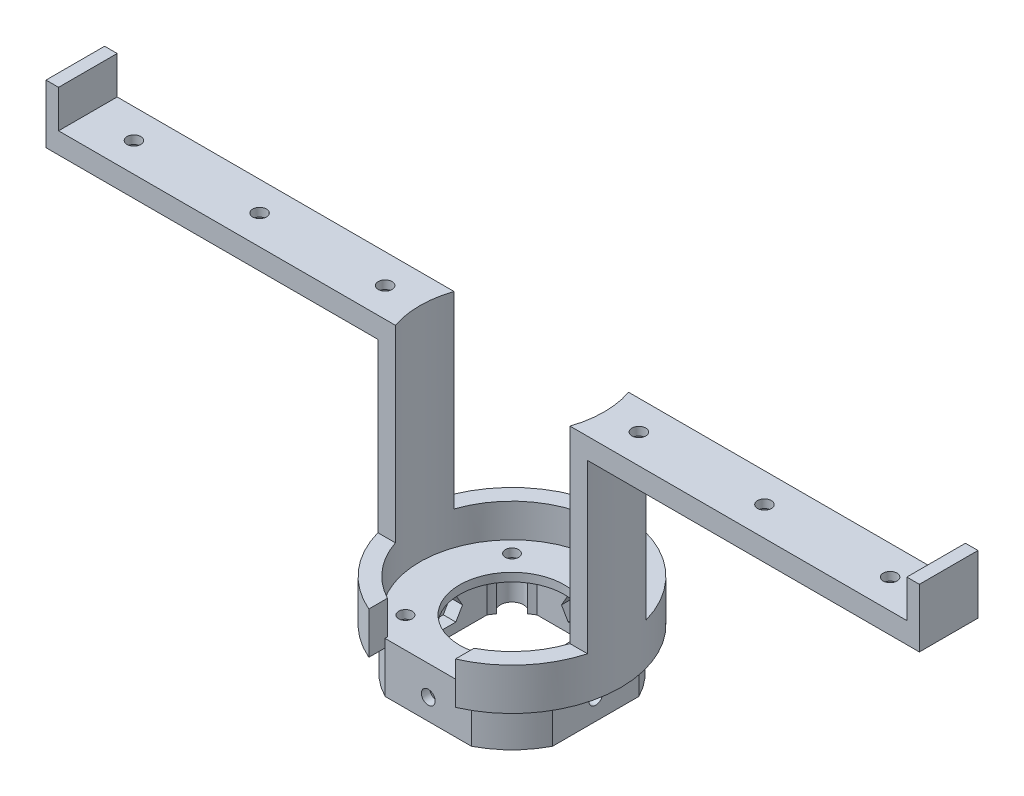
SolidWorks part; units mm, degrees
ref_plane "前视基准面" through (0, 0, 0) normal (0, 0, 1) x (1, 0, 0)
ref_plane "上视基准面" through (0, 0, 0) normal (0, 1, 0) x (1, 0, 0)
ref_plane "右视基准面" through (0, 0, 0) normal (1, 0, 0) x (0, 0, -1)
sketch "草图1" plane through (0, 0, 0) normal (0, 1, 0) x (1, 0, 0)
  line L0 (0, 0) -> (0, 18) construction
  line L1 (0, 0) -> (12.7279, 12.7279) construction
  line L2 (-32.6893, 0) -> (36.6315, 0) construction
  arc A0 (-20.3411, 8.381) -> (20.3411, 8.381) centre (0, 0) ccw
  circle A1 centre (0, 0) radius 18 construction
  circle A2 centre (12.7279, 12.7279) radius 1.6
  circle A3 centre (12.7279, -12.7279) radius 1.6
  circle A4 centre (-12.7279, -12.7279) radius 1.6
  circle A5 centre (-12.7279, 12.7279) radius 1.6
  circle A6 centre (0, 0) radius 22
  arc A7 (20.3411, 8.381) -> (-20.3411, 8.381) centre (0, 0) ccw
  point P16 (0, 0)
  dimension "D1" = 44
  dimension "D2" = 36
  dimension "D3" = 45
  dimension "D4" = 3.2
  dimension "D5" = 4
extrude "凸台-拉伸1" add sketch "草图1" along normal blind 2 contours A0 A6 A2 A3 A4 A5
sketch "草图2" plane through (0, 2, 0) normal (0, 1, 0) x (1, 0, 0)
  circle A1 centre (0, 0) radius 12.5
  dimension "D1" = 25
extrude "切除-拉伸1" cut sketch "草图2" against normal blind 3 contours A1
sketch "草图5" plane through (0, 0, 0) normal (0, 1, 0) x (1, 0, 0)
  line L6 (0, 27.5) -> (0, -27.5) construction
  circle A1 centre (0, 0) radius 22
  circle A3 centre (0, 0) radius 26
  dimension "D3" = 44
  dimension "D1" = 52
extrude "凸台-拉伸3" add sketch "草图5" along normal blind 10
sketch "草图14" plane through (0, 0, 0) normal (0, -1, 0) x (1, 0, 0)
  line L0 (-10.3078, 20) -> (10.3078, 20)
  line L1 (20, 10.3078) -> (20, -10.3078)
  line L2 (-10.3078, -20) -> (10.3078, -20)
  line L3 (-20, -10.3078) -> (-20, 10.3078)
  line L4 (-9.0139, 15) -> (9.0139, 15)
  line L5 (15, 9.0139) -> (15, -9.0139)
  line L6 (-15, 9.0139) -> (-15, -9.0139)
  line L7 (-9.0139, -15) -> (9.0139, -15)
  arc A0 (-10.3078, 20) -> (-20, 10.3078) centre (0, 0) ccw
  arc A1 (20, 10.3078) -> (10.3078, 20) centre (0, 0) ccw
  arc A2 (10.3078, -20) -> (20, -10.3078) centre (0, 0) ccw
  arc A3 (-20, -10.3078) -> (-10.3078, -20) centre (0, 0) ccw
  arc A4 (-15, -9.0139) -> (-14.1106, -10.3508) centre (0, 0) ccw
  arc A5 (-9.0139, 15) -> (-10.3508, 14.1106) centre (0, 0) ccw
  arc A6 (15, 9.0139) -> (14.1106, 10.3508) centre (0, 0) ccw
  arc A7 (9.0139, -15) -> (10.3508, -14.1106) centre (0, 0) ccw
  arc A8 (-10.3508, 14.1106) -> (-14.1106, 10.3508) centre (-12.7279, 12.7279) ccw
  arc A9 (14.1106, 10.3508) -> (10.3508, 14.1106) centre (12.7279, 12.7279) ccw
  arc A10 (-14.1106, -10.3508) -> (-10.3508, -14.1106) centre (-12.7279, -12.7279) ccw
  arc A11 (10.3508, -14.1106) -> (14.1106, -10.3508) centre (12.7279, -12.7279) ccw
  arc A12 (-14.1106, 10.3508) -> (-15, 9.0139) centre (0, 0) ccw
  arc A13 (10.3508, 14.1106) -> (9.0139, 15) centre (0, 0) ccw
  arc A14 (-10.3508, -14.1106) -> (-9.0139, -15) centre (0, 0) ccw
  arc A15 (14.1106, -10.3508) -> (15, -9.0139) centre (0, 0) ccw
  dimension "D1" = 45
  dimension "D6" = 35
  dimension "D11" = 5.5
  dimension "D12" = 5.5
  dimension "D13" = 5.5
  dimension "D14" = 5.5
  dimension "D2" = 20
  dimension "D3" = 20
  dimension "D4" = 20
  dimension "D5" = 20
  dimension "D7" = 5
  dimension "D8" = 5
  dimension "D9" = 5
  dimension "D10" = 5
extrude "凸台-拉伸5" add sketch "草图14" along normal blind 10
sketch "草图15" plane through (-20, 0, 0) normal (-1, 0, 0) x (0, 0, 1)
  line L0 (10.3078, 0) -> (-10.3078, 0) construction
  line L3 (0, 0) -> (0, -10) construction
  line L4 (10.3078, -10) -> (-10.3078, -10) construction
  circle A0 centre (0, -5) radius 1.65
  dimension "D1" = 3.3
  dimension "D2" = 5
extrude "切除-拉伸2" cut sketch "草图15" against normal blind 42
sketch "草图16" plane through (0, 0, -20) normal (0, 0, -1) x (-1, 0, 0)
  line L0 (10.3078, 0) -> (-10.3078, 0) construction
  line L1 (0, 0) -> (0, -10) construction
  line L2 (10.3078, -10) -> (-10.3078, -10) construction
  circle A0 centre (0, -5) radius 1.65
  dimension "D1" = 3.3
  dimension "D2" = 5
extrude "切除-拉伸3" cut sketch "草图16" against normal blind 42
sketch "草图18" plane through (0, 0, 0) normal (0, 0, 1) x (1, 0, 0)
  line L1 (-1.5877, -2.25) -> (-3.1754, -5)
  line L2 (-3.1754, -5) -> (-1.5877, -7.75)
  line L3 (-1.5877, -7.75) -> (1.5877, -7.75)
  line L4 (1.5877, -7.75) -> (3.1754, -5)
  line L5 (3.1754, -5) -> (1.5877, -2.25)
  line L6 (1.5877, -2.25) -> (-1.5877, -2.25)
  circle A0 centre (0, -5) radius 2.75 construction
  dimension "D1" = 5.5
extrude "切除-拉伸4" cut sketch "草图18" against normal mid plane 36
sketch "草图19" plane through (0, 0, 0) normal (1, 0, 0) x (0, 0, -1)
  line L1 (-1.5877, -2.25) -> (-3.1754, -5)
  line L2 (-3.1754, -5) -> (-1.5877, -7.75)
  line L3 (-1.5877, -7.75) -> (1.5877, -7.75)
  line L4 (1.5877, -7.75) -> (3.1754, -5)
  line L5 (3.1754, -5) -> (1.5877, -2.25)
  line L6 (1.5877, -2.25) -> (-1.5877, -2.25)
  circle A0 centre (0, -5) radius 2.75 construction
  dimension "D1" = 5.5
extrude "切除-拉伸5" cut sketch "草图19" against normal mid plane 36
sketch "草图23" plane through (0, 10, 0) normal (0, 1, 0) x (1, 0, 0)
  line L0 (-20.8567, 7) -> (-25.04, 7)
  line L1 (-26, 0) -> (26, 0) construction
  line L2 (-20.8567, -7) -> (-25.04, -7)
  line L3 (20.8567, 7) -> (25.04, 7)
  line L4 (20.8567, -7) -> (25.04, -7)
  circle A0 centre (0, 0) radius 22 construction
  circle A1 centre (0, 0) radius 26 construction
  circle A2 centre (0, 0) radius 26
  circle A3 centre (0, 0) radius 22 construction
  circle A4 centre (0, 0) radius 22
  circle M8 centre (0, 0) radius 26
  circle M9 centre (0, 0) radius 22
  dimension "D1" = 7
  dimension "D2" = 7
  dimension "D3" = 7
extrude "凸台-拉伸6" add sketch "草图23" along normal blind 45 contours L1 A4 L0 M8 | L1 A2 L2 M9 | L1 A2 L3 M9 | L1 A4 L4 M8
sketch "草图24" plane through (0, 55, 0) normal (0, 1, 0) x (1, 0, 0)
  line L0 (-20.8567, 7) -> (-25.04, 7) construction
  line L1 (-25.04, -7) -> (-75.3, -7)
  line L2 (-25.04, -7) -> (-25.04, 7)
  line L3 (-25.04, 7) -> (-75.3, 7)
  line L4 (-75.3, -7) -> (-75.3, 7)
  dimension "D1" = 50.26
extrude "凸台-拉伸7" add sketch "草图24" against normal blind 5
mirror "镜向1" about plane through (0, 0, 0) normal (1, 0, 0) of "凸台-拉伸7"
sketch "草图25" plane through (0, 55, 0) normal (0, 1, 0) x (1, 0, 0)
  line L0 (-75.3, 7) -> (-75.3, -7) construction
  line L2 (-22, 0) -> (-75.3, 0) construction
  circle A0 centre (-60.3, 0) radius 1.65
  arc A1 (-20.8567, 7) -> (-20.8567, -7) centre (0, 0) ccw construction
  circle A2 centre (-30.3, 0) radius 1.65
  dimension "D1" = 3.3
  dimension "D3" = 3.3
  dimension "D2" = 15
  dimension "D4" = 30
extrude "切除-拉伸6" cut sketch "草图25" against normal blind 5
sketch "草图26" plane through (0, 50, 0) normal (0, 1, 0) x (1, 0, 0)
  line L1 (-58.7123, 2.75) -> (-61.8877, 2.75)
  line L2 (-61.8877, 2.75) -> (-63.4754, 0)
  line L3 (-63.4754, 0) -> (-61.8877, -2.75)
  line L4 (-61.8877, -2.75) -> (-58.7123, -2.75)
  line L5 (-58.7123, -2.75) -> (-57.1245, 0)
  line L6 (-57.1245, 0) -> (-58.7123, 2.75)
  line L7 (-31.8877, 2.75) -> (-33.4754, 0)
  line L8 (-33.4754, 0) -> (-31.8877, -2.75)
  line L9 (-31.8877, -2.75) -> (-28.7123, -2.75)
  line L10 (-28.7123, -2.75) -> (-27.1245, 0)
  line L11 (-27.1245, 0) -> (-28.7123, 2.75)
  line L12 (-28.7123, 2.75) -> (-31.8877, 2.75)
  circle A0 centre (-60.3, 0) radius 2.75 construction
  circle A1 centre (-30.3, 0) radius 2.75 construction
  dimension "D1" = 5.5
  dimension "D2" = 5.5
extrude "切除-拉伸7" cut sketch "草图26" along normal blind 3
mirror "镜向3" about plane through (0, 0, 0) normal (1, 0, 0) of "切除-拉伸6", "切除-拉伸7"
sketch "草图28" plane through (0, 0, 0) normal (0, -1, 0) x (1, 0, 0)
  line L0 (-10.34, 20) -> (10.34, 20)
  line L1 (10.3078, 20) -> (-10.3078, 20) construction
  line L2 (10.34, 20) -> (10.34, 23.8555)
  line L3 (-10.34, 20) -> (-10.34, 23.8555)
  line L4 (0, 26) -> (0, -26) construction
  line L5 (-26, 0) -> (26, 0) construction
  circle A0 centre (0, 0) radius 26 construction
  arc A2 (10.34, 23.8555) -> (-10.34, 23.8555) centre (0, 0) ccw
  point P4 (0, 20)
  dimension "D1" = 20.68
extrude "切除-拉伸9" cut sketch "草图28" against normal blind 10
sketch "草图29" plane through (0, 10, 0) normal (0, 1, 0) x (1, 0, 0)
  line L6 (-10.34, -20) -> (-10.34, -19.4187)
  line L7 (10.34, -20) -> (10.34, -19.4187)
  line L8 (9.1652, -20) -> (10.34, -20) construction
  line L9 (9.1652, -20) -> (10.34, -20)
  line L10 (-10.34, -20) -> (-9.1652, -20) construction
  line L11 (-10.34, -20) -> (-9.1652, -20)
  circle A6 centre (0, 0) radius 22 construction
  circle A7 centre (0, 0) radius 22 construction
  arc A8 (-10.34, -19.4187) -> (-9.1652, -20) centre (0, 0) ccw
  arc A9 (9.1652, -20) -> (10.34, -19.4187) centre (0, 0) ccw
extrude "切除-拉伸10" cut sketch "草图29" against normal blind 8
sketch "草图34" plane through (0, 50, 0) normal (0, -1, 0) x (1, 0, 0)
  line L0 (-75.3, 0) -> (75.3, 0) construction
  line L1 (-75.3, -7) -> (-101.3, -7)
  line L2 (-75.3, -7) -> (-75.3, 7)
  line L3 (-75.3, 7) -> (-101.3, 7)
  line L4 (-101.3, -7) -> (-101.3, 7)
  line L5 (75.3, -7) -> (101.3, -7)
  line L6 (75.3, -7) -> (75.3, 7)
  line L7 (75.3, 7) -> (101.3, 7)
  line L8 (101.3, -7) -> (101.3, 7)
  line L9 (-75.3, -7) -> (-75.3, 7) construction
  line L10 (75.3, -7) -> (75.3, 7) construction
  line L12 (-75.3, 7) -> (-25.04, 7) construction
  line L13 (75.3, 7) -> (25.04, 7) construction
  point P14 (-75.3, 0)
  point P17 (75.3, 0)
  dimension "D1" = 26
  dimension "D2" = 26
extrude "凸台-拉伸9" add sketch "草图34" against normal blind 5
sketch "草图35" plane through (0, 55, 0) normal (0, 1, 0) x (1, 0, 0)
  circle A0 centre (-90.3, 0) radius 1.65
  circle A1 centre (90.3, 0) radius 1.65
  circle A2 centre (-60.3, 0) radius 1.65 construction
  circle A3 centre (60.3, 0) radius 1.65 construction
  dimension "D3" = 3.3
  dimension "D4" = 3.3
  dimension "D1" = 30
  dimension "D2" = 30
extrude "切除-拉伸11" cut sketch "草图35" against normal blind 5
sketch "草图36" plane through (0, 50, 0) normal (0, -1, 0) x (1, 0, 0)
  line L1 (-91.8877, 2.75) -> (-93.4754, 0)
  line L2 (-93.4754, 0) -> (-91.8877, -2.75)
  line L3 (-91.8877, -2.75) -> (-88.7123, -2.75)
  line L4 (-88.7123, -2.75) -> (-87.1245, 0)
  line L5 (-87.1245, 0) -> (-88.7123, 2.75)
  line L6 (-88.7123, 2.75) -> (-91.8877, 2.75)
  line L7 (91.8877, 2.75) -> (88.7123, 2.75)
  line L8 (88.7123, 2.75) -> (87.1245, 0)
  line L9 (87.1245, 0) -> (88.7123, -2.75)
  line L10 (88.7123, -2.75) -> (91.8877, -2.75)
  line L11 (91.8877, -2.75) -> (93.4754, 0)
  line L12 (93.4754, 0) -> (91.8877, 2.75)
  circle A0 centre (-90.3, 0) radius 2.75 construction
  circle A1 centre (90.3, 0) radius 2.75 construction
  dimension "D1" = 5.5
  dimension "D2" = 5.5
extrude "切除-拉伸12" cut sketch "草图36" against normal blind 3
sketch "草图37" plane through (0, 50, 0) normal (0, -1, 0) x (1, 0, 0)
  line L0 (-101.3, 7) -> (-25.04, 7) construction
  line L1 (-101.3, -7) -> (-104.3, -7)
  line L2 (-101.3, -7) -> (-101.3, 7)
  line L3 (-101.3, 7) -> (-104.3, 7)
  line L4 (-104.3, -7) -> (-104.3, 7)
  line L5 (101.3, 7) -> (25.04, 7) construction
  line L6 (101.3, -7) -> (104.3, -7)
  line L7 (101.3, -7) -> (101.3, 7)
  line L8 (101.3, 7) -> (104.3, 7)
  line L9 (104.3, -7) -> (104.3, 7)
  dimension "D1" = 3
  dimension "D2" = 3
extrude "凸台-拉伸10" add sketch "草图37" against normal blind 14
